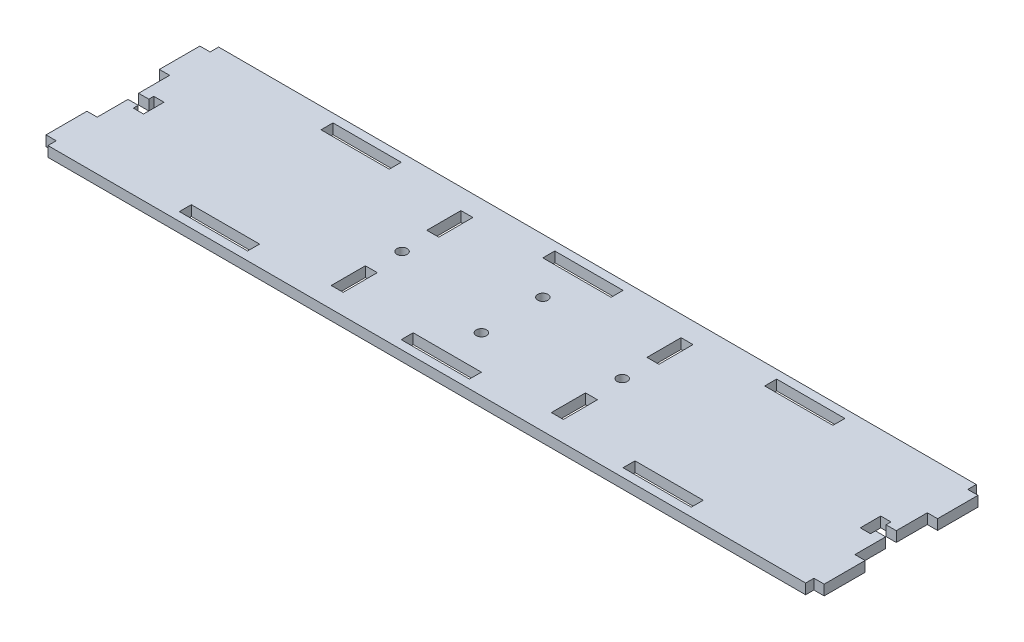
SolidWorks part; units mm, degrees
ref_plane "Alzado" through (0, 0, 0) normal (0, 0, 1) x (1, 0, 0)
ref_plane "Planta" through (0, 0, 0) normal (0, 1, 0) x (1, 0, 0)
ref_plane "Vista lateral" through (0, 0, 0) normal (1, 0, 0) x (0, 0, -1)
sketch "Croquis1" plane through (0, 0, 0) normal (0, 1, 0) x (1, 0, 0)
  line L0 (-111, 0) -> (-105, 0) construction
  line L1 (111, -25) -> (-111, -25)
  line L2 (111, -25) -> (111, -1.55)
  line L3 (111, 25) -> (-111, 25)
  line L4 (-111, -25) -> (-111, -1.55)
  line L5 (111, -25) -> (-111, 25) construction
  line L6 (111, 25) -> (-111, -25) construction
  line L7 (-111, 1.55) -> (-108, 1.55)
  line L8 (-108, 1.55) -> (-108, 3)
  line L9 (-108, 3) -> (-105, 3)
  line L10 (-105, 3) -> (-105, -3)
  line L11 (-108, -3) -> (-105, -3)
  line L12 (-108, -1.55) -> (-108, -3)
  line L13 (-111, -1.55) -> (-108, -1.55)
  line L14 (-111, 1.55) -> (-111, 25)
  line L15 (0, 0) -> (0, 25) construction
  line L16 (111, 1.55) -> (108, 1.55)
  line L17 (108, 1.55) -> (108, 3)
  line L18 (108, 3) -> (105, 3)
  line L19 (105, 3) -> (105, -3)
  line L20 (108, -1.55) -> (108, -3)
  line L21 (111, -1.55) -> (108, -1.55)
  line L22 (108, -3) -> (105, -3)
  line L23 (111, 1.55) -> (111, 25)
  line L24 (55, 22.5) -> (55, 19)
  line L25 (-10, 22.5) -> (10, 22.5)
  line L26 (-10, 22.5) -> (-10, 19)
  line L27 (-10, 19) -> (10, 19)
  line L28 (10, 22.5) -> (10, 19)
  line L29 (-10, 22.5) -> (10, 19) construction
  line L30 (-10, 19) -> (10, 22.5) construction
  line L31 (55, 22.5) -> (75, 22.5)
  line L32 (75, 22.5) -> (75, 19)
  line L33 (55, 19) -> (75, 19)
  line L34 (-10, 22.5) -> (55, 22.5) construction
  line L35 (-55, 22.5) -> (-75, 22.5)
  line L36 (-75, 22.5) -> (-75, 19)
  line L37 (-55, 19) -> (-75, 19)
  line L38 (-55, 22.5) -> (-55, 19)
  line L39 (0, 0) -> (-105, 0) construction
  line L40 (55, -22.5) -> (75, -22.5)
  line L41 (75, -22.5) -> (75, -19)
  line L42 (55, -19) -> (75, -19)
  line L43 (55, -22.5) -> (55, -19)
  line L44 (-10, -19) -> (10, -19)
  line L45 (10, -22.5) -> (10, -19)
  line L46 (-10, -22.5) -> (10, -22.5)
  line L47 (-10, -22.5) -> (-10, -19)
  line L48 (-55, -22.5) -> (-55, -19)
  line L49 (-55, -19) -> (-75, -19)
  line L50 (-75, -22.5) -> (-75, -19)
  line L51 (-55, -22.5) -> (-75, -22.5)
  line L52 (-34, 9) -> (-30.5, 9)
  line L53 (-34, -19) -> (-30.5, -19)
  line L54 (-34, -19) -> (-34, -9)
  line L55 (-34, -9) -> (-30.5, -9)
  line L56 (-30.5, -19) -> (-30.5, -9)
  line L57 (-34, -19) -> (-30.5, -9) construction
  line L58 (-34, -9) -> (-30.5, -19) construction
  line L59 (-30.5, 19) -> (-30.5, 9)
  line L60 (-34, 19) -> (-30.5, 19)
  line L61 (-34, 19) -> (-34, 9)
  line L62 (34, 19) -> (34, 9)
  line L63 (34, 19) -> (30.5, 19)
  line L64 (30.5, 19) -> (30.5, 9)
  line L65 (34, 9) -> (30.5, 9)
  line L66 (34, -9) -> (30.5, -9)
  line L67 (30.5, -19) -> (30.5, -9)
  line L68 (34, -19) -> (30.5, -19)
  line L69 (34, -19) -> (34, -9)
  circle A0 centre (-32.25, 0) radius 1.5
  circle A1 centre (32.25, 0) radius 1.5
  circle A2 centre (0, -9) radius 1.5
  circle A3 centre (0, 9) radius 1.5
  point P0 (0, 0)
  point P26 (0, 20.75)
  point P53 (-32.25, -14)
  point P73 (-32.25, 9)
  dimension "D16" = 3
  dimension "D17" = 3
  dimension "D1" = 222
  dimension "D2" = 50
  dimension "D3" = 6
  dimension "D4" = 3
  dimension "D5" = 1.55
  dimension "D6" = 3
  dimension "D7" = 3.5
  dimension "D8" = 20
  dimension "D9" = 2.5
  dimension "D11" = 45
  dimension "D12" = 6
  dimension "D13" = 3.5
  dimension "D14" = 10
  dimension "D15" = 77
  dimension "D18" = 16
  dimension "D10" = 2
extrude "Saliente-Extruir1" add sketch "Croquis1" along normal blind 3
sketch "Croquis2" plane through (-111, 0, 0) normal (-1, 0, 0) x (0, 0, 1)
  line L0 (-16.575, 3.25) -> (-16.575, -0.25) construction
  line L1 (-10.575, 3.25) -> (-22.575, 3.25) construction
  line L2 (-22.575, -0.25) -> (-10.575, -0.25) construction
  line L3 (-22.575, 1.5) -> (-10.575, 1.5) construction
  line L4 (-22.575, 3.25) -> (-22.575, -0.25) construction
  line L5 (-10.575, -0.25) -> (-10.575, 3.25) construction
  line L6 (-22.5, 3) -> (-10.575, 3) construction
  line L7 (-25, 3) -> (-1.55, 3) construction
  line L8 (16.575, 3.25) -> (16.575, -0.25) construction
  line L9 (-10.65, 0) -> (-22.5, 0)
  line L10 (-10.65, 0) -> (-10.65, 3)
  line L11 (-10.65, 3) -> (-22.5, 3)
  line L12 (-22.5, 0) -> (-22.5, 3)
  line L13 (-10.65, 0) -> (-22.5, 3) construction
  line L14 (-10.65, 3) -> (-22.5, 0) construction
  line L15 (22.575, 3.25) -> (10.575, 3.25) construction
  line L16 (10.575, -0.25) -> (22.575, -0.25) construction
  line L17 (10.575, 3.25) -> (22.575, 3.25) construction
  line L18 (10.575, 3.25) -> (10.575, -0.25) construction
  line L19 (22.575, 0) -> (10.575, 0)
  line L20 (22.575, 0) -> (22.575, 3)
  line L21 (22.575, 3) -> (10.575, 3)
  line L22 (10.575, 0) -> (10.575, 3)
  line L23 (22.575, 0) -> (10.575, 3) construction
  line L24 (22.575, 3) -> (10.575, 0) construction
  line L25 (1.55, 3) -> (25, 3) construction
  point P17 (-16.575, 1.5)
  point P31 (16.575, 1.5)
extrude "Saliente-Extruir2" add sketch "Croquis2" along normal blind 3
mirror "Simetría1" about plane through (0, 0, 0) normal (1, 0, 0) of "Saliente-Extruir2"
